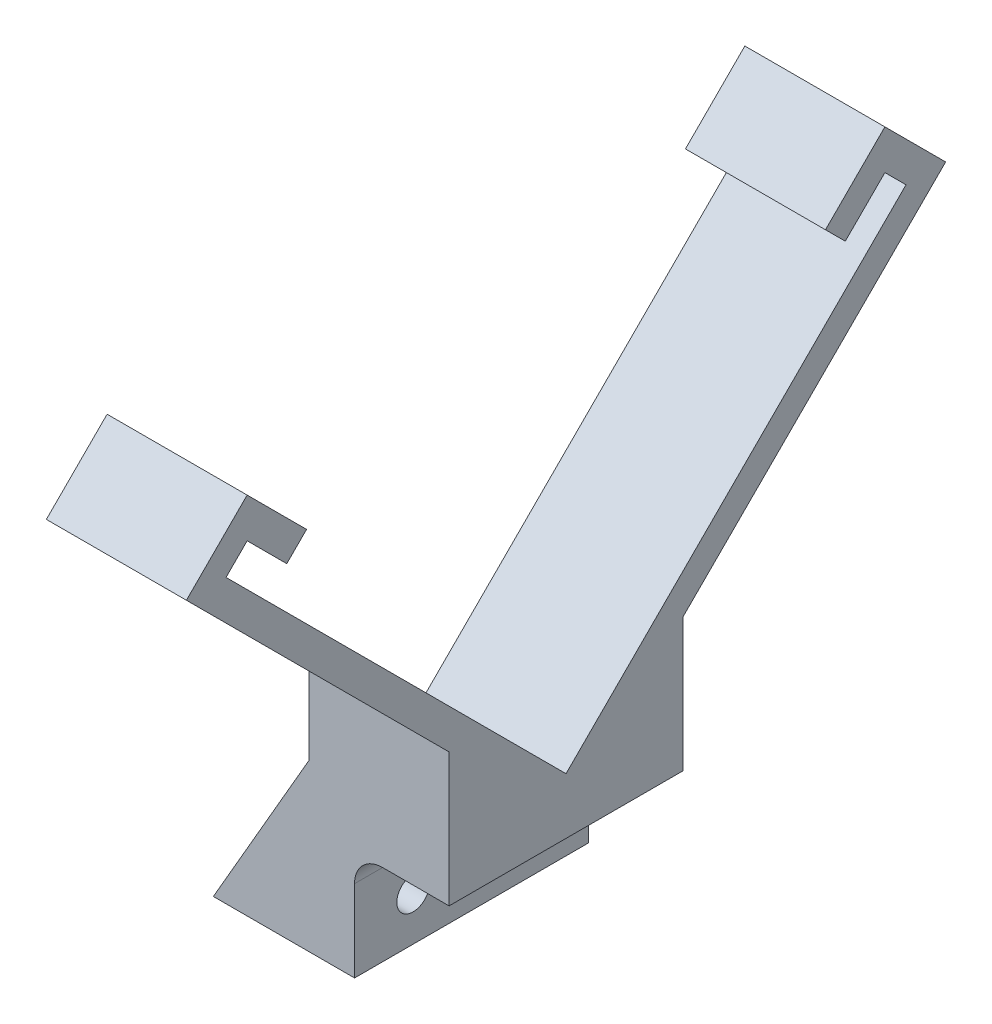
SolidWorks part; units mm, degrees
ref_plane "Front Plane" through (0, 0, 0) normal (0, 0, 1) x (1, 0, 0)
ref_plane "Top Plane" through (0, 0, 0) normal (0, 1, 0) x (1, 0, 0)
ref_plane "Right Plane" through (0, 0, 0) normal (1, 0, 0) x (0, 0, -1)
sketch "Sketch1" plane through (0, 0, 0) normal (0, 0, 1) x (1, 0, 0)
  line L1 (0, 0) -> (-10.248, -17.75)
  line L2 (-10.248, -17.75) -> (4.876, -17.75)
  line L3 (4.876, -17.75) -> (4.876, -6)
  line L4 (4.876, -6) -> (15, -6)
  line L5 (15, -6) -> (15, 0)
  line L7 (4.876, -13) -> (-14.4338, -13) construction
  line L8 (0, 0) -> (-6.9282, 0) construction
  line L9 (-6.9282, 0) -> (-17.1762, -17.75) construction
  line L10 (-17.1762, -17.75) -> (-10.248, -17.75) construction
  line L11 (-5.124, -8.875) -> (4.876, -8.875) construction
  line L12 (15, 0) -> (0, 0)
  dimension "D4" = 15
  dimension "D1" = 60
  dimension "D2" = 6
  dimension "D3" = 10
  dimension "D5" = 4.75
  dimension "D7" = 7
  dimension "D9" = 6
extrude "Boss-Extrude1" add sketch "Sketch1" along normal blind 25.05
sketch "Sketch3" plane through (4.876, 0, 0) normal (1, 0, 0) x (0, 0, -1)
  line L0 (-25.05, -13) -> (-18.775, -13) construction
  line L2 (-18.775, -13) -> (-6.275, -13) construction
  line L3 (-6.275, -13) -> (0, -13) construction
  line L5 (0, -17.75) -> (0, -6) construction
  line L6 (-25.05, -17.75) -> (-25.05, -6) construction
  circle A0 centre (-18.775, -13) radius 1.75
  circle A1 centre (-6.275, -13) radius 1.75
  dimension "D1" = 3.5
  dimension "D2" = 12.5
  dimension "D3" = 4.75
extrude "Cut-Extrude2" cut sketch "Sketch3" against normal through all
fillet "Fillet1" radius 3 1 edges at (4.876, -6, 12.525)
sketch "Sketch4" plane through (15, 0, 0) normal (1, 0, 0) x (0, 0, -1)
  line L0 (-25.05, 8.2824) -> (-53.1836, 36.416)
  line L1 (-25.05, 0) -> (0, 0) construction
  line L2 (-53.1836, 36.416) -> (-46.6783, 42.9214)
  line L3 (-46.6783, 42.9214) -> (-40.3143, 36.5574)
  line L4 (-40.3143, 36.5574) -> (-42.4356, 34.4361)
  line L5 (-42.4356, 34.4361) -> (-46.6783, 38.6787)
  line L6 (-46.6783, 38.6787) -> (-48.941, 36.416)
  line L7 (-48.941, 36.416) -> (-12.525, 0)
  line L8 (-12.525, 0) -> (23.891, 36.416)
  line L9 (23.891, 36.416) -> (21.6283, 38.6787)
  line L10 (21.6283, 38.6787) -> (17.3856, 34.4361)
  line L11 (17.3856, 34.4361) -> (15.2643, 36.5574)
  line L12 (15.2643, 36.5574) -> (21.6283, 42.9214)
  line L13 (21.6283, 42.9214) -> (28.1336, 36.416)
  line L14 (28.1336, 36.416) -> (0, 8.2824)
  line L15 (0, 8.2824) -> (0, -6)
  line L16 (0, -6) -> (-25.05, -6)
  line L17 (-51.0623, 34.2947) -> (-48.941, 36.416) construction
  line L18 (-48.941, 36.416) -> (-51.0623, 38.5373) construction
  line L19 (26.0123, 34.2947) -> (23.891, 36.416) construction
  line L20 (26.0123, 38.5373) -> (23.891, 36.416) construction
  line L21 (-25.05, -6) -> (-25.05, 8.2824)
  dimension "D1" = 3
  dimension "D2" = 3.2
  dimension "D3" = 51.5
  dimension "D4" = 6
extrude "Boss-Extrude2" add sketch "Sketch4" against normal up to vertex (15 mm away)
